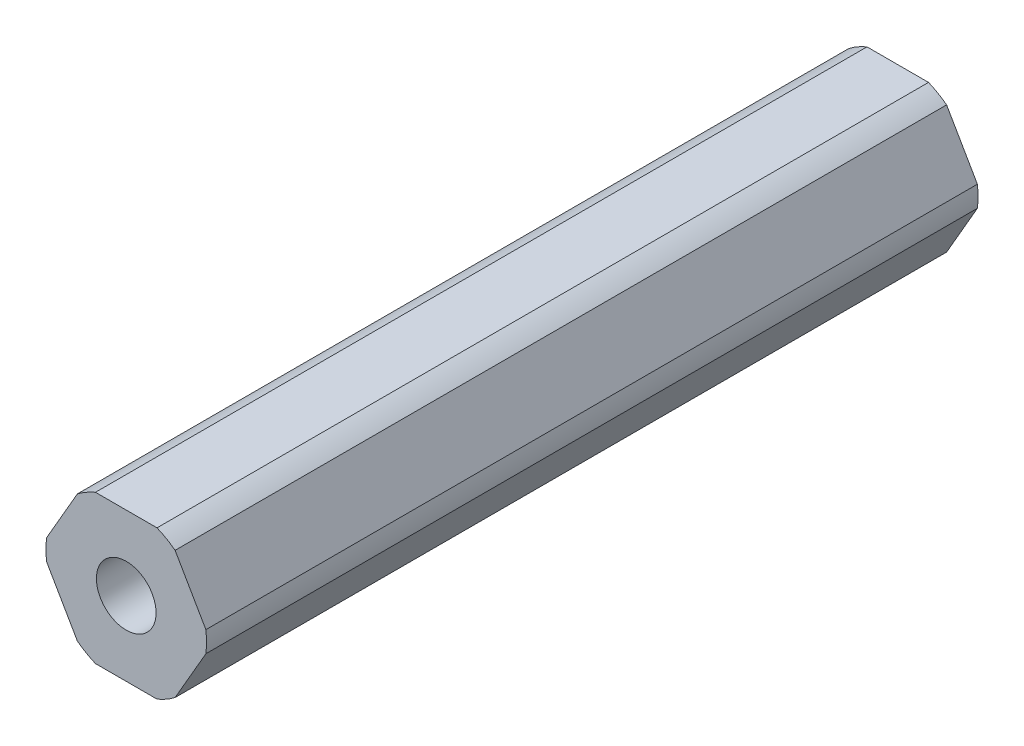
SolidWorks part; units mm, degrees
ref_plane "Front" through (0, 0, 0) normal (0, 0, 1) x (1, 0, 0)
ref_plane "Top" through (0, 0, 0) normal (0, 1, 0) x (1, 0, 0)
ref_plane "Right" through (0, 0, 0) normal (1, 0, 0) x (0, 0, -1)
sketch "Sketch1" plane through (0, 0, 0) normal (0, 0, 1) x (1, 0, 0)
  line L1 (6.8168, 0.893) -> (4.1818, 5.457)
  line L2 (2.635, 6.35) -> (-2.635, 6.35)
  line L3 (-4.1818, 5.457) -> (-6.8168, 0.893)
  line L4 (-6.8168, -0.893) -> (-4.1818, -5.457)
  line L5 (-2.635, -6.35) -> (2.635, -6.35)
  line L6 (4.1818, -5.457) -> (6.8168, -0.893)
  arc A0 (-6.8168, 0.893) -> (-6.8168, -0.893) centre (0, 0) ccw
  circle A1 centre (0, 0) radius 6.35 construction
  arc A2 (-4.1818, -5.457) -> (-2.635, -6.35) centre (0, 0) ccw
  arc A3 (2.635, -6.35) -> (4.1818, -5.457) centre (0, 0) ccw
  arc A4 (6.8168, -0.893) -> (6.8168, 0.893) centre (0, 0) ccw
  arc A5 (4.1818, 5.457) -> (2.635, 6.35) centre (0, 0) ccw
  arc A6 (-2.635, 6.35) -> (-4.1818, 5.457) centre (0, 0) ccw
  circle A7 centre (0, 0) radius 2.5527
  dimension "D1" = 13.75
  dimension "D2" = 12.7
  dimension "D3" = 5.1054
extrude "Boss-Extrude1" add sketch "Sketch1" along normal blind 66.04
